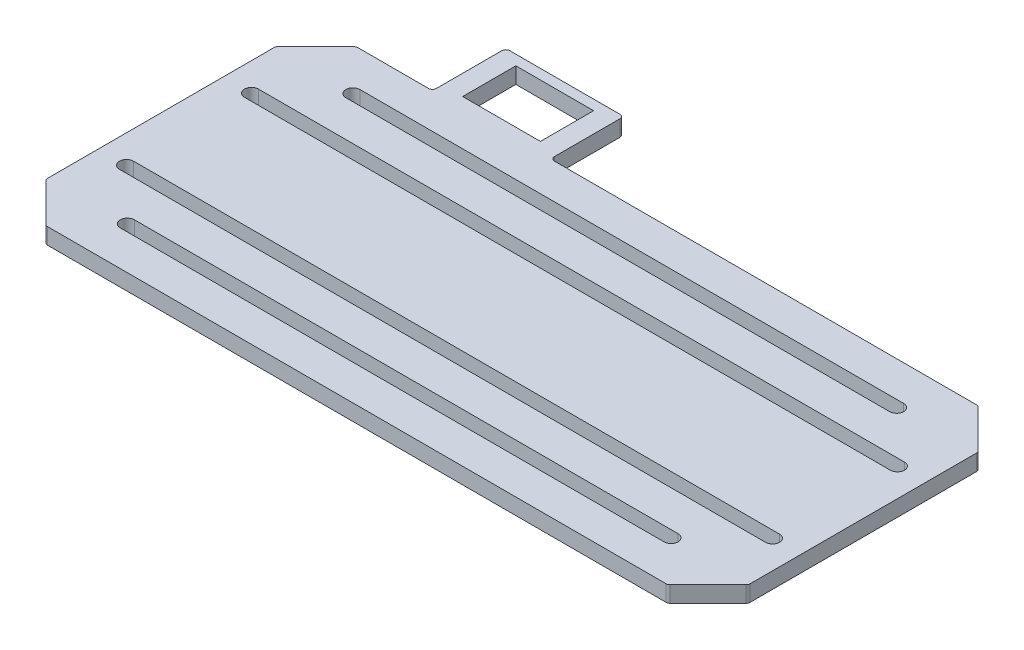
SolidWorks part; units mm, degrees
ref_plane "Front Plane" through (0, 0, 0) normal (0, 0, 1) x (1, 0, 0)
ref_plane "Top Plane" through (0, 0, 0) normal (0, 1, 0) x (1, 0, 0)
ref_plane "Right Plane" through (0, 0, 0) normal (1, 0, 0) x (0, 0, -1)
sketch "Sketch2" plane through (0, 0, 0) normal (0, 1, 0) x (1, 0, 0)
  line L1 (87.185, -38.5) -> (-87.185, -38.5)
  line L2 (87.185, -38.5) -> (87.185, 38.5)
  line L3 (87.185, 38.5) -> (-87.185, 38.5)
  line L4 (-87.185, -38.5) -> (-87.185, 38.5)
  line L5 (87.185, -38.5) -> (-87.185, 38.5) construction
  line L6 (87.185, 38.5) -> (-87.185, -38.5) construction
  point P0 (0, 0)
  dimension "D1" = 77
  dimension "D2" = 174.37
extrude "Boss-Extrude1" add sketch "Sketch2" along normal blind 4
sketch "Sketch3" plane through (0, 4, 0) normal (0, 1, 0) x (1, 0, 0)
  line L0 (-87.185, 0) -> (87.185, 0) construction
  line L1 (-87.185, 38.5) -> (-87.185, -38.5) construction
  line L2 (87.185, -38.5) -> (87.185, 38.5) construction
  line L8 (-67.5, 29.75) -> (67.5, 29.75)
  line L26 (67.5, 26.25) -> (-67.5, 26.25)
  line L29 (-67.5, -29.75) -> (67.5, -29.75)
  line L30 (67.5, -26.25) -> (-67.5, -26.25)
  arc A0 (-67.5, 29.75) -> (-67.5, 26.25) centre (-67.5, 28) ccw
  arc A1 (67.5, 26.25) -> (67.5, 29.75) centre (67.5, 28) ccw
  arc A10 (67.5, -26.25) -> (67.5, -29.75) centre (67.5, -28) cw
  arc A12 (-67.5, -29.75) -> (-67.5, -26.25) centre (-67.5, -28) cw
  point P15 (0, 26.25)
  dimension "D2" = 56
  dimension "D1" = 3.5
  dimension "D3" = 135
extrude "Cut-Extrude1" cut sketch "Sketch3" against normal up to vertex (4 mm away) up to point (0, 0, 0)
sketch "Sketch4" plane through (0, 0, 0) normal (0, -1, 0) x (1, 0, 0)
  line L0 (87.185, -38.5) -> (-87.185, -38.5) construction
  line L1 (-58.2425, -38.5) -> (-28.9425, -38.5)
  line L2 (-58.2425, -38.5) -> (-58.2425, -56.7)
  line L3 (-58.2425, -56.7) -> (-28.9425, -56.7)
  line L4 (-28.9425, -38.5) -> (-28.9425, -56.7)
  line L6 (-33.9425, -54.2) -> (-53.2425, -54.2)
  line L7 (-33.9425, -54.2) -> (-33.9425, -41)
  line L8 (-33.9425, -41) -> (-53.2425, -41)
  line L9 (-53.2425, -54.2) -> (-53.2425, -41)
  line L10 (-33.9425, -54.2) -> (-53.2425, -41) construction
  line L11 (-33.9425, -41) -> (-53.2425, -54.2) construction
  line L12 (0, 0) -> (-87.185, 0) construction
  line L13 (-87.185, -38.5) -> (-87.185, 38.5) construction
  line L14 (-43.5925, 0) -> (-43.5925, -38.5) construction
  line L15 (87.185, -38.5) -> (-87.185, -38.5) construction
  point P6 (-43.5925, -47.6)
  point P11 (-58.2425, -47.6)
  point P21 (0, 0)
  point P22 (-43.5925, -38.5)
  dimension "D1" = 19.3
  dimension "D2" = 13.2
  dimension "D3" = 5
  dimension "D4" = 2.5
  dimension "D5" = 5
extrude "Boss-Extrude2" add sketch "Sketch4" against normal up to surface (4 mm away) up to face at (0, 4, -28)
chamfer "Chamfer1" distance 10 angle 45 4 edges at (-87.185, 2, -38.5) (87.185, 2, -38.5) (87.185, 2, 38.5) (-87.185, 2, 38.5)
fillet "Fillet1" radius 1 12 edges at (-58.2425, 2, -38.5) (-58.2425, 2, -56.7) (-28.9425, 2, -56.7) (-28.9425, 2, -38.5) (87.185, 2, -28.5) (77.185, 2, -38.5) (77.185, 2, 38.5) (87.185, 2, 28.5) (-77.185, 2, 38.5) (-87.185, 2, 28.5) (-87.185, 2, -28.5) (-77.185, 2, -38.5)
sketch "Sketch5" plane through (0, 4, 0) normal (0, 1, 0) x (1, 0, 0)
  line L0 (-87.185, 0) -> (87.185, 0) construction
  line L1 (-87.185, 28.0858) -> (-87.185, -28.0858) construction
  line L2 (87.185, -28.0858) -> (87.185, 28.0858) construction
  line L3 (0, -38.5) -> (0, 38.5) construction
  line L4 (-76.7708, -38.5) -> (76.7708, -38.5) construction
  line L6 (-80.185, 13.75) -> (80.185, 13.75)
  line L7 (80.185, 17.25) -> (-80.185, 17.25)
  line L8 (80.185, -17.25) -> (-80.185, -17.25)
  line L9 (-80.185, -13.75) -> (80.185, -13.75)
  line L10 (76.7708, 38.5) -> (-27.9425, 38.5) construction
  arc A0 (-80.185, 17.25) -> (-80.185, 13.75) centre (-80.185, 15.5) ccw
  arc A3 (80.185, 17.25) -> (80.185, 13.75) centre (80.185, 15.5) cw
  arc A4 (-80.185, -17.25) -> (-80.185, -13.75) centre (-80.185, -15.5) cw
  arc A5 (80.185, -17.25) -> (80.185, -13.75) centre (80.185, -15.5) ccw
  point P10 (0, 38.5)
  dimension "D1" = 3.5
  dimension "D3" = 7
  dimension "D2" = 31
extrude "Cut-Extrude2" cut sketch "Sketch5" against normal blind 10
